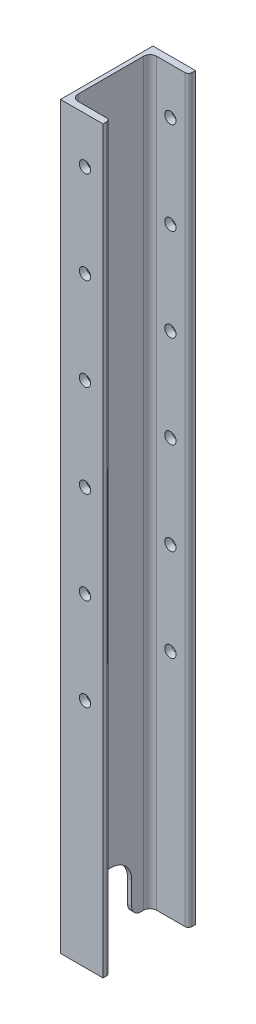
SolidWorks part; units mm, degrees
material "Сталь 3 ГОСТ 535-88"
ref_plane "Спереди" through (0, 0, 0) normal (0, 0, 1) x (1, 0, 0)
ref_plane "Сверху" through (0, 0, 0) normal (0, 1, 0) x (1, 0, 0)
ref_plane "Справа" through (0, 0, 0) normal (1, 0, 0) x (0, 0, -1)
other "Configuration Table"
sketch "Эскиз1" plane through (0, 0, 0) normal (0, 1, 0) x (1, 0, 0)
  line L0 (0, -50) -> (0, 50)
  line L1 (0, 50) -> (46, 50)
  line L2 (46, 50) -> (46, 46.4)
  line L3 (42, 42.4) -> (11.5, 42.4)
  line L4 (4.5, 35.4) -> (4.5, -35.4)
  line L5 (11.5, -42.4) -> (42, -42.4)
  line L6 (46, -46.4) -> (46, -50)
  line L7 (46, -50) -> (0, -50)
  arc A0 (4.5, -35.4) -> (11.5, -42.4) centre (11.5, -35.4) ccw
  arc A1 (11.5, 42.4) -> (4.5, 35.4) centre (11.5, 35.4) ccw
  arc A2 (42, -42.4) -> (46, -46.4) centre (42, -46.4) cw
  arc A3 (46, 46.4) -> (42, 42.4) centre (42, 46.4) cw
  point P4 (0, 0)
  point P19 (46, 42.4)
  dimension "D5" = 7
  dimension "D6" = 4
  dimension "D1" = 100
  dimension "D2" = 46
  dimension "D3" = 7.6
  dimension "D4" = 4.5
extrude "Бобышка-Вытянуть1" add sketch "Эскиз1" along normal blind 800
sketch "Эскиз2" plane through (0, 0, 0) normal (-1, 0, 0) x (0, 0, 1)
  line L0 (0, 0) -> (0, 35) construction
  line L1 (0, -50) -> (0, 50) construction
  line L2 (-22.5, 35) -> (-22.5, 0)
  line L3 (-50, 0) -> (50, 0) construction
  line L4 (-22.5, 0) -> (22.5, 0)
  line L5 (22.5, 0) -> (22.5, 35)
  arc A0 (22.5, 35) -> (-22.5, 35) centre (0, 35) ccw
  dimension "D2" = 22.5
  dimension "D1" = 35
extrude "Вырез-Вытянуть1" cut sketch "Эскиз2" against normal through all both and the other way through all
fillet "Скругление1" radius 10 2 edges at (2.25, 0, -22.5) (2.25, 0, 22.5)
sketch "Эскиз3" plane through (0, 0, -50) normal (0, 0, -1) x (-1, 0, 0)
  line L0 (-46, 800) -> (0, 800) construction
  line L3 (0, 800) -> (0, 0) construction
  circle A5 centre (-26.44, 750) radius 6.1
  circle A6 centre (-26.44, 650) radius 6.1
  circle A7 centre (-26.44, 550) radius 6.1
  circle A8 centre (-26.44, 450) radius 6.1
  circle A9 centre (-26.44, 350) radius 6.1
  circle A10 centre (-26.44, 250) radius 6.1
  dimension "D1" = 12.2
  dimension "D2" = 50
  dimension "D3" = 6
  dimension "D4" = 26.44
  dimension "D5" = 100
extrude "Вырез-Вытянуть2" cut sketch "Эскиз3" against normal through all both and the other way through all
